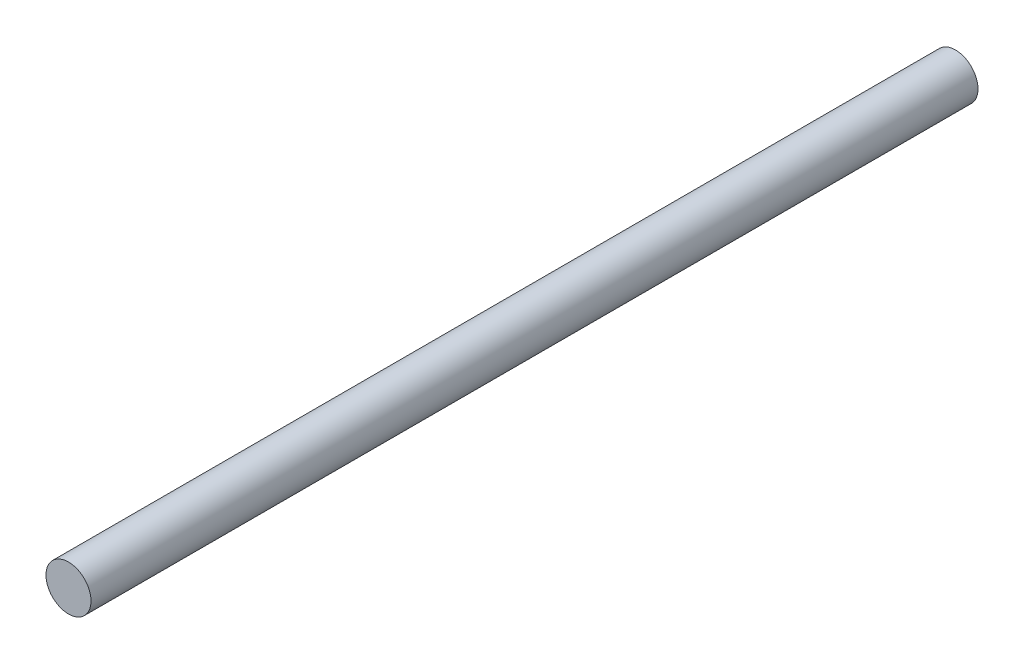
SolidWorks part; units mm, degrees
ref_plane "Front Plane" through (0, 0, 0) normal (0, 0, 1) x (1, 0, 0)
ref_plane "Top Plane" through (0, 0, 0) normal (0, 1, 0) x (1, 0, 0)
ref_plane "Right Plane" through (0, 0, 0) normal (1, 0, 0) x (0, 0, -1)
sketch "Sketch2" plane through (0, 0, 0) normal (0, 0, 1) x (1, 0, 0)
  circle A0 centre (0, 0) radius 6.35
  dimension "D1" = 12.7
extrude "Boss-Extrude1" add sketch "Sketch2" along normal blind 250
